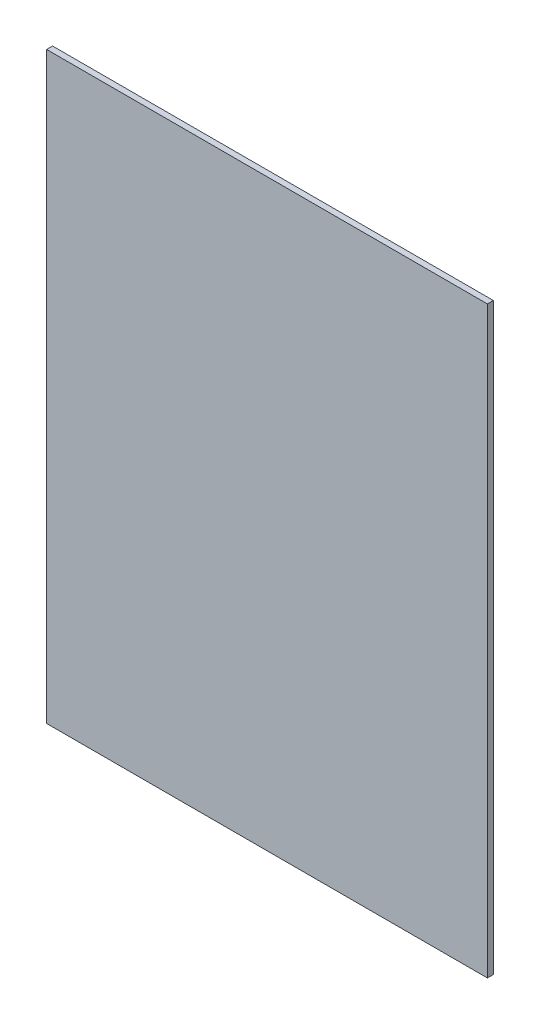
SolidWorks part; units mm, degrees
material "Glass"
ref_plane "Front Plane" through (0, 0, 0) normal (0, 0, 1) x (1, 0, 0)
ref_plane "Top Plane" through (0, 0, 0) normal (0, 1, 0) x (1, 0, 0)
ref_plane "Right Plane" through (0, 0, 0) normal (1, 0, 0) x (0, 0, -1)
sketch "Sketch1" plane through (0, 0, 0) normal (0, 0, 1) x (1, 0, 0)
  line L1 (-117.475, -155.575) -> (117.475, -155.575)
  line L2 (-117.475, -155.575) -> (-117.475, 155.575)
  line L3 (-117.475, 155.575) -> (117.475, 155.575)
  line L4 (117.475, -155.575) -> (117.475, 155.575)
  line L5 (-117.475, -155.575) -> (117.475, 155.575) construction
  line L6 (-117.475, 155.575) -> (117.475, -155.575) construction
  point P0 (0, 0)
  dimension "D1" = 311.15
  dimension "D2" = 234.95
extrude "Boss-Extrude1" add sketch "Sketch1" along normal blind 3.175
